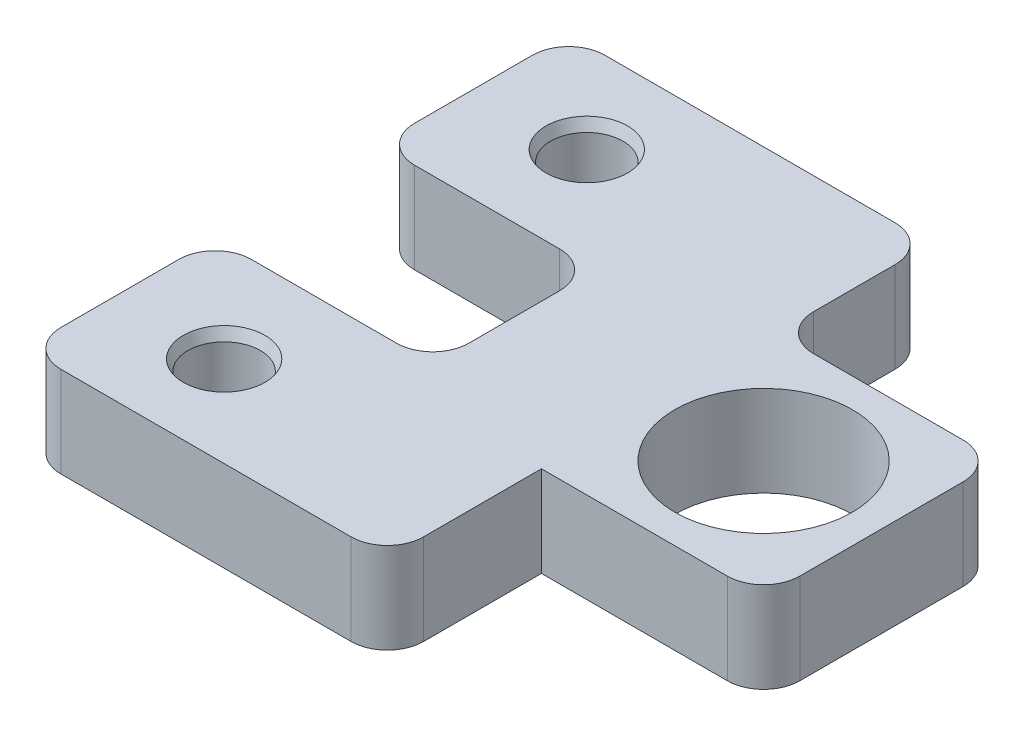
SolidWorks part; units mm, degrees
ref_plane "Front Plane" through (0, 0, 0) normal (0, 0, 1) x (1, 0, 0)
ref_plane "Top Plane" through (0, 0, 0) normal (0, 1, 0) x (1, 0, 0)
ref_plane "Right Plane" through (0, 0, 0) normal (1, 0, 0) x (0, 0, -1)
sketch "Sketch1" plane through (0, 0, 0) normal (0, 1, 0) x (1, 0, 0)
  line L0 (-10, 4.5) -> (-10, -4.5)
  line L1 (-10, -15) -> (10, -15)
  line L2 (-10, -15) -> (-10, 15)
  line L3 (-10, 15) -> (10, 15)
  line L4 (10, -15) -> (10, 15)
  line L5 (-10, -15) -> (10, 15) construction
  line L6 (-10, 15) -> (10, -15) construction
  line L7 (-10, 4.5) -> (2, 4.5)
  line L8 (2, 4.5) -> (2, -4.5)
  line L9 (2, -4.5) -> (-10, -4.5)
  line L10 (10, 0) -> (21.5, 0) construction
  line L12 (9.25, -6.5) -> (22.25, -6.5)
  line L13 (9.25, -6.5) -> (9.25, 6.5)
  line L14 (9.25, 6.5) -> (22.25, 6.5)
  line L15 (22.25, -6.5) -> (22.25, 6.5)
  line L16 (9.25, -6.5) -> (22.25, 6.5) construction
  line L17 (9.25, 6.5) -> (22.25, -6.5) construction
  circle A0 centre (15.75, 0) radius 4.9
  point P0 (0, 0)
  point P9 (-10, 0)
  dimension "D6" = 9.8
  dimension "D1" = 30
  dimension "D2" = 20
  dimension "D3" = 9
  dimension "D4" = 12
  dimension "D5" = 11.5
  dimension "D7" = 13
extrude "Boss-Extrude1" add sketch "Sketch1" along normal blind 5 contours L8 L9 L2 L1 L4 L3 L7 | L12 L15 L14 L4 A0 | L14 L13 L12 L4
fillet "Fillet1" radius 2 11 edges at (10, 2.5, -6.5) (10, 2.5, -15) (-10, 2.5, -15) (-10, 2.5, -4.5) (2, 2.5, -4.5) (2, 2.5, 4.5) (-10, 2.5, 4.5) (-10, 2.5, 15) (22.25, 2.5, -6.5) (22.25, 2.5, 6.5) (10, 2.5, 15)
sketch "Sketch4" plane through (0, 5, 0) normal (0, 1, 0) x (1, 0, 0)
  line L0 (0, 0) -> (-4, 0) construction
  line L1 (-4, 10) -> (-4, -10) construction
  point P4 (-4, -10)
  point P5 (-4, 10)
  point P6 (-4, 0)
  dimension "D1" = 4
  dimension "D2" = 10
hole_wizard "Ø4.0 (4) Diameter Hole1" positions "Sketch4" profile "Sketch5" hole size "Ø4.0" standard "ANSI Metric" end condition up to next
sketch "Sketch5" plane through (-4, 5, 0) normal (1, 0, 0) x (0, 0, 1)
  line L0 (0, 0) -> (0, 5)
  line L1 (0, 5) -> (2, 5)
  line L2 (2, 5) -> (2, 0.6036)
  line L3 (2, 0.6036) -> (2.25, 0)
  line L5 (2.25, 0) -> (0, 0)
  line L6 (-2, 0.6036) -> (-2.25, 0) construction
  line L11 (0, -6.35) -> (0, 107.95) construction
  dimension "Thru Hole Dia." = 4
  dimension "Thru Hole Depth" = 5
  dimension "Near C'Sink Dia." = 4.5
  dimension "Near C'Sink Angle" = 45
